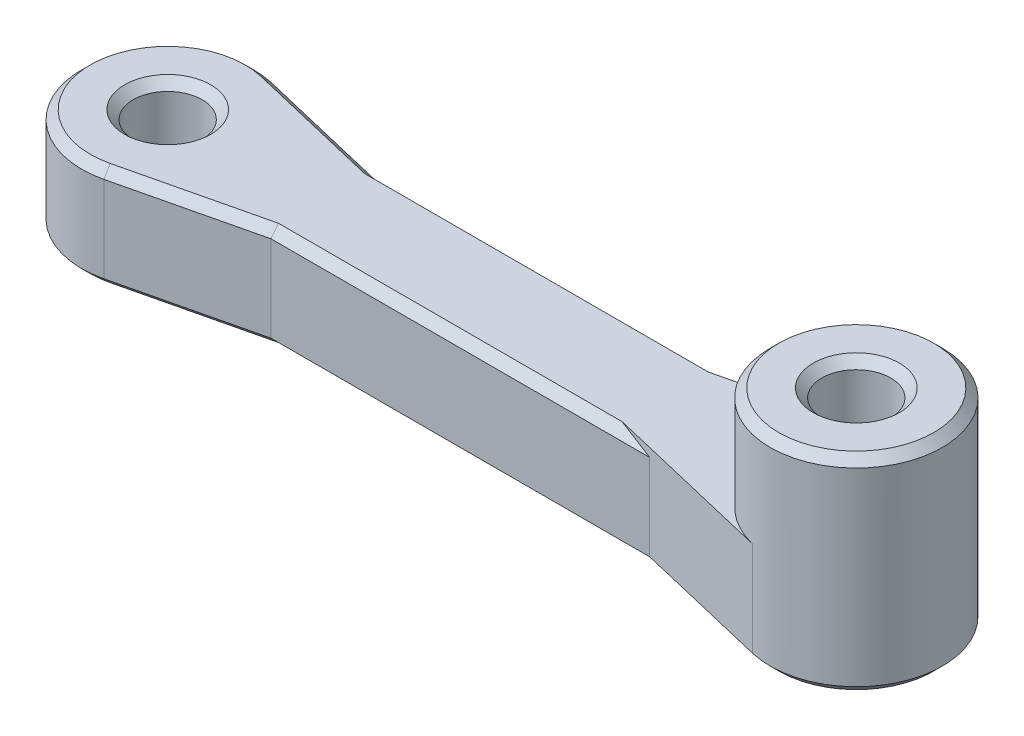
SolidWorks part; units mm, degrees
ref_plane "前视基准面" through (0, 0, 0) normal (0, 0, 1) x (1, 0, 0)
ref_plane "上视基准面" through (0, 0, 0) normal (0, 1, 0) x (1, 0, 0)
ref_plane "右视基准面" through (0, 0, 0) normal (1, 0, 0) x (0, 0, -1)
other "Configuration Table"
sketch "草图1" plane through (0, 0, 0) normal (0, 1, 0) x (1, 0, 0)
  line L0 (0, 0) -> (20, 0) construction
  line L1 (2, 1.5) -> (18, 1.5)
  line L2 (18, -1.5) -> (2, -1.5)
  arc A0 (2, 1.5) -> (2, -1.5) centre (0, 0) ccw
  arc A1 (18, -1.5) -> (18, 1.5) centre (20, 0) ccw
  dimension "D1" = 5
  dimension "D3" = 5
  dimension "D2" = 20
  dimension "D4" = 3
extrude "凸台-拉伸1" add sketch "草图1" along normal blind 3
sketch "草图2" plane through (0, 0, 0) normal (0, 1, 0) x (1, 0, 0)
  circle A0 centre (0, 0) radius 1
  circle A1 centre (20, 0) radius 1
  dimension "D1" = 2
  dimension "D2" = 2
extrude "切除-拉伸1" cut sketch "草图2" along normal up to surface (3 mm away) up to face at (10, 3, 0)
sketch "草图3" plane through (0, 0, 0) normal (0, 1, 0) x (1, 0, 0)
  line L0 (4.5, 1.5) -> (0.5781, 2.4322)
  line L1 (4.5, -1.5) -> (0.5781, -2.4322)
  line L2 (2, -1.5) -> (18, -1.5)
  line L3 (18, 1.5) -> (2, 1.5)
  line L4 (2, -1.5) -> (4.5, -1.5)
  line L5 (18, 1.5) -> (15.5, 1.5)
  line L6 (15.5, 1.5) -> (19.4219, 2.4322)
  line L7 (15.5, -1.5) -> (19.4219, -2.4322)
  line L8 (15.5, -1.5) -> (18, -1.5)
  line L9 (4.5, 1.5) -> (2, 1.5)
  arc A0 (0.5781, -2.4322) -> (2, -1.5) centre (0, 0) ccw
  arc A1 (19.4219, 2.4322) -> (18, 1.5) centre (20, 0) ccw
  arc A2 (2, 1.5) -> (2, -1.5) centre (0, 0) ccw
  arc A3 (18, -1.5) -> (18, 1.5) centre (20, 0) ccw
  arc A4 (2, 1.5) -> (0.5781, 2.4322) centre (0, 0) ccw
  arc A5 (18, -1.5) -> (19.4219, -2.4322) centre (20, 0) ccw
  dimension "D2" = 2.5
  dimension "D3" = 2.5
  dimension "D4" = 2.5
  dimension "D5" = 2.5
  dimension "D1" = 0
extrude "凸台-拉伸2" add sketch "草图3" along normal up to surface (3 mm away) up to face at (0, 3, 1)
chamfer "倒角1" distance 0.25 angle 45 10 edges at (20, 0, 1) (0, 0, 1) (10, 0, -1.5) (2.5391, 0, -1.9661) (-2.5, 0, 0) (2.5391, 0, 1.9661) (10, 0, 1.5) (17.4609, 0, 1.9661) (22.5, 0, 0) (17.4609, 0, -1.9661)
sketch "草图4" plane through (0, 0, 0) normal (0, 1, 0) x (1, 0, 0)
  circle A0 centre (20, 0) radius 1
  circle A1 centre (20, 0) radius 2.5
  dimension "D1" = 5
  dimension "D2" = 2
extrude "凸台-拉伸3" add sketch "草图4" along normal blind 3 from surface at 3 starting at face at (10, 3, 0)
chamfer "倒角3" distance 0.25 angle 45 8 edges at (20, 6, 2.5) (20, 6, 1) (0, 3, 1) (10, 3, -1.5) (2.5391, 3, -1.9661) (-2.5, 3, 0) (2.5391, 3, 1.9661) (10, 3, 1.5)
